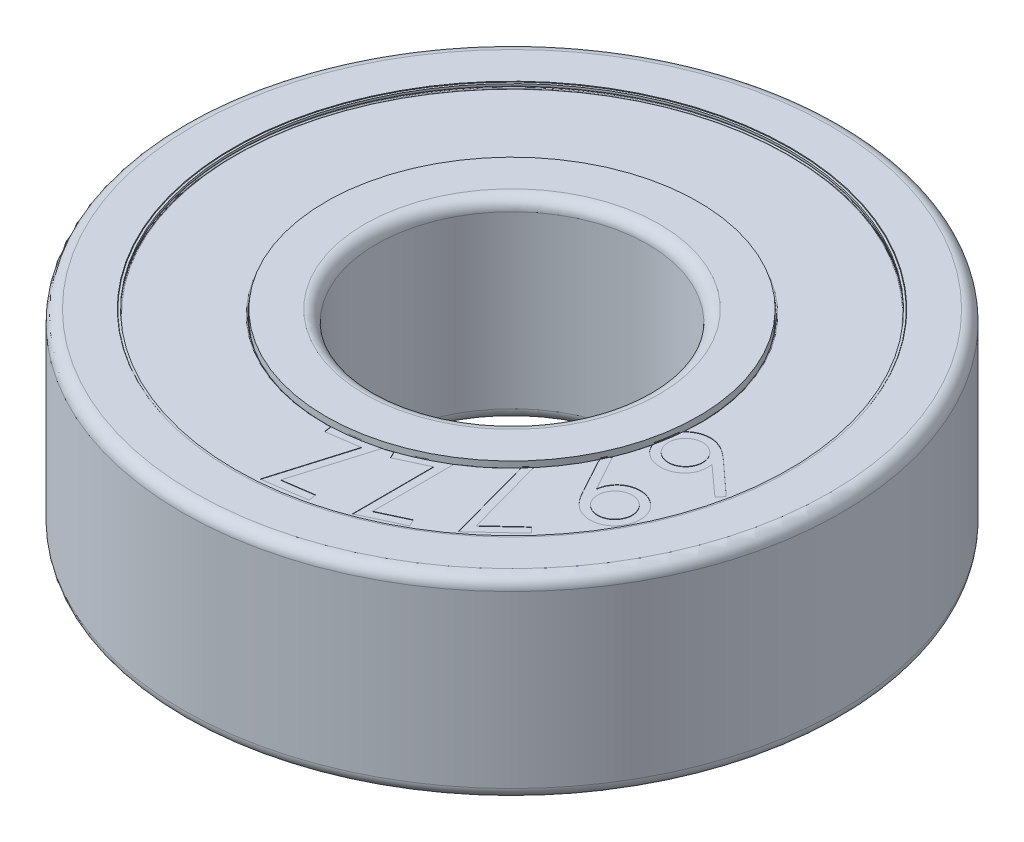
SolidWorks part; units mm, degrees
ref_plane "Front Plane" through (0, 0, 0) normal (0, 0, 1) x (1, 0, 0)
ref_plane "Top Plane" through (0, 0, 0) normal (0, 1, 0) x (1, 0, 0)
ref_plane "Right Plane" through (0, 0, 0) normal (1, 0, 0) x (0, 0, -1)
sketch "Croquis1" plane through (0, 0, 0) normal (1, 0, 0) x (0, 0, -1)
  line L0 (0, 5.6806) -> (0, -4.3073) construction
  line L1 (0, 0) -> (7.85, 0) construction
  line L2 (4.8, -2.5) -> (3.8, -2.5)
  line L3 (4.8, -2.5) -> (4.8, -0.9)
  line L4 (4.8, 2.5) -> (3.8, 2.5)
  line L5 (3.5, -2.2) -> (3.5, 2.2)
  line L6 (4.8, -2.5) -> (3.5, 2.5) construction
  line L7 (4.8, 2.5) -> (3.5, -2.5) construction
  line L8 (8.2, -2.5) -> (7.2, -2.5)
  line L9 (8.5, -2.2) -> (8.5, 2.2)
  line L10 (8.2, 2.5) -> (7.2, 2.5)
  line L11 (7.2, -2.5) -> (7.2, -2.45)
  line L12 (8.5, -2.5) -> (7.2, 2.5) construction
  line L13 (8.5, 2.5) -> (7.2, -2.5) construction
  line L14 (4.8, 0) -> (7.2, 0) construction
  line L15 (4.8, 0.9) -> (4.8, 2.5)
  line L16 (7.2, 0.9) -> (7.2, 2.1784)
  line L17 (7.2, -2.1784) -> (7.3884, -2.2877)
  line L18 (7.3884, -2.3525) -> (7.2, -2.45)
  line L19 (7.2, -2.1784) -> (7.2, -0.9)
  line L20 (7.2, 2.1784) -> (7.3884, 2.2877)
  line L21 (7.3884, 2.3525) -> (7.2, 2.45)
  line L22 (7.2, 2.45) -> (7.2, 2.5)
  line L23 (6, 0) -> (6, -0.5097) construction
  arc A0 (4.8, 0.9) -> (4.8, -0.9) centre (6, 0) ccw
  arc A1 (7.2, -0.9) -> (7.2, 0.9) centre (6, 0) ccw
  arc A2 (8.2, -2.5) -> (8.5, -2.2) centre (8.2, -2.2) ccw
  arc A3 (8.5, 2.2) -> (8.2, 2.5) centre (8.2, 2.2) ccw
  arc A4 (3.8, 2.5) -> (3.5, 2.2) centre (3.8, 2.2) ccw
  arc A5 (3.8, -2.5) -> (3.5, -2.2) centre (3.8, -2.2) cw
  arc A6 (7.3884, -2.3525) -> (7.3884, -2.2877) centre (7.3696, -2.3201) ccw
  arc A7 (7.3884, 2.3525) -> (7.3884, 2.2877) centre (7.3696, 2.3201) cw
  point P3 (4.15, 0)
  point P8 (7.85, 0)
  dimension "D6" = 3
  dimension "D7" = 0.3
  dimension "D1" = 3.5
  dimension "D2" = 8.5
  dimension "D3" = 5
  dimension "D4" = 1.3
  dimension "D5" = 1.3
  dimension "D8" = 0.05
  dimension "D9" = 6
revolve "Revolución1" add sketch "Croquis1" angle 360 about L0
sketch "Croquis3" plane through (0, 0, 0) normal (1, 0, 0) x (0, 0, -1)
  line L0 (0, 2.5) -> (0, -2.5) construction
  line L2 (-3.8, -2.5) -> (3.8, -2.5) construction
  line L3 (0, 0) -> (8.4869, 0) construction
  line L4 (3.8, 2.5) -> (-3.8, 2.5) construction
  line L5 (6, 2.5) -> (6, -2.5) construction
  line L6 (6, 1.475) -> (6, -1.475)
  arc A1 (6, -1.475) -> (6, 1.475) centre (6, 0) ccw
  point P2 (6, 0)
  dimension "D3" = 2.95
  dimension "D1" = 6
  dimension "D2" = 5
revolve "Revolución3" add sketch "Croquis3" angle 360 about L5
sketch "Croquis4" plane through (0, 0, 0) normal (1, 0, 0) x (0, 0, -1)
  line L0 (7.1909, -2.4866) -> (7.1909, -2.4681)
  line L1 (7.207, -2.4416) -> (7.387, -2.3472)
  line L2 (7.3881, -2.2947) -> (7.2209, -2.1972)
  line L3 (7.1799, -2.208) -> (7.1217, -2.3079)
  line L4 (7.0957, -2.3228) -> (4.8868, -2.3228)
  line L5 (4.8579, -2.3012) -> (4.8496, -2.2725)
  line L6 (4.8496, -2.2725) -> (4.8016, -2.2864)
  line L7 (4.8016, -2.2864) -> (4.8204, -2.3512)
  line L8 (4.8492, -2.3728) -> (7.1245, -2.3728)
  line L9 (7.1504, -2.3579) -> (7.1971, -2.2777)
  line L10 (7.2382, -2.2669) -> (7.2833, -2.2932)
  line L11 (7.2822, -2.3457) -> (7.157, -2.4113)
  line L12 (7.1409, -2.4379) -> (7.1409, -2.4866)
  line L13 (7.1409, -2.4866) -> (7.1909, -2.4866)
  line L14 (0, 0) -> (8.2183, 0) construction
  line L15 (5.0552, -1.2107) -> (5.0552, -1.3218)
  line L16 (-7.2, -2.45) -> (7.2, -2.45) construction
  line L17 (6.8464, 1.2792) -> (6.8464, 1.3848)
  line L18 (0, 1.5186) -> (0, -1.2233) construction
  line L19 (6.8464, -1.2792) -> (6.8464, -1.3848)
  line L20 (5.0552, 1.2107) -> (5.0552, 1.3218)
  line L21 (7.1409, 2.4866) -> (7.1909, 2.4866)
  line L22 (7.1409, 2.4379) -> (7.1409, 2.4866)
  line L23 (7.2822, 2.3457) -> (7.157, 2.4113)
  line L24 (7.2382, 2.2669) -> (7.2833, 2.2932)
  line L25 (7.1504, 2.3579) -> (7.1971, 2.2777)
  line L26 (4.8492, 2.3728) -> (7.1245, 2.3728)
  line L27 (4.8016, 2.2864) -> (4.8204, 2.3512)
  line L28 (4.8496, 2.2725) -> (4.8016, 2.2864)
  line L29 (4.8579, 2.3012) -> (4.8496, 2.2725)
  line L30 (7.0957, 2.3228) -> (4.8868, 2.3228)
  line L31 (7.1799, 2.208) -> (7.1217, 2.3079)
  line L32 (7.3881, 2.2947) -> (7.2209, 2.1972)
  line L33 (7.207, 2.4416) -> (7.387, 2.3472)
  line L34 (7.1909, 2.4866) -> (7.1909, 2.4681)
  arc A0 (4.8868, -2.3228) -> (4.8579, -2.3012) centre (4.8868, -2.2928) cw
  arc A1 (4.8204, -2.3512) -> (4.8492, -2.3728) centre (4.8492, -2.3428) ccw
  arc A2 (7.1971, -2.2777) -> (7.2382, -2.2669) centre (7.2231, -2.2928) cw
  arc A3 (7.2209, -2.1972) -> (7.1799, -2.208) centre (7.2058, -2.2231) ccw
  arc A4 (7.1909, -2.4681) -> (7.207, -2.4416) centre (7.2209, -2.4681) cw
  arc A5 (7.157, -2.4113) -> (7.1409, -2.4379) centre (7.1709, -2.4379) ccw
  arc A6 (7.2833, -2.2932) -> (7.2822, -2.3457) centre (7.2682, -2.3191) cw
  arc A7 (7.387, -2.3472) -> (7.3881, -2.2947) centre (7.373, -2.3206) ccw
  arc A8 (7.1245, -2.3728) -> (7.1504, -2.3579) centre (7.1245, -2.3428) ccw
  arc A9 (7.1217, -2.3079) -> (7.0957, -2.3228) centre (7.0957, -2.2928) cw
  arc A10 (5.0681, -1.3465) -> (6.8316, -1.4106) centre (6, 0) ccw
  arc A11 (5.1032, -1.1868) -> (6.8002, -1.2539) centre (6, 0) ccw
  arc A12 (6.8464, -1.3848) -> (6.8316, -1.4106) centre (6.8164, -1.3848) cw
  arc A13 (6.8002, -1.2539) -> (6.8464, -1.2792) centre (6.8164, -1.2792) cw
  arc A14 (5.0681, -1.3465) -> (5.0552, -1.3218) centre (5.0852, -1.3218) cw
  arc A15 (5.0552, -1.2107) -> (5.1032, -1.1868) centre (5.0852, -1.2107) cw
  arc A16 (5.0552, 1.2107) -> (5.1032, 1.1868) centre (5.0852, 1.2107) ccw
  arc A17 (5.0681, 1.3465) -> (5.0552, 1.3218) centre (5.0852, 1.3218) ccw
  arc A18 (6.8002, 1.2539) -> (6.8464, 1.2792) centre (6.8164, 1.2792) ccw
  arc A19 (6.8464, 1.3848) -> (6.8316, 1.4106) centre (6.8164, 1.3848) ccw
  arc A20 (5.1032, 1.1868) -> (6.8002, 1.2539) centre (6, 0) cw
  arc A21 (5.0681, 1.3465) -> (6.8316, 1.4106) centre (6, 0) cw
  arc A22 (7.1217, 2.3079) -> (7.0957, 2.3228) centre (7.0957, 2.2928) ccw
  arc A23 (7.1245, 2.3728) -> (7.1504, 2.3579) centre (7.1245, 2.3428) cw
  arc A24 (7.387, 2.3472) -> (7.3881, 2.2947) centre (7.373, 2.3206) cw
  arc A25 (7.2833, 2.2932) -> (7.2822, 2.3457) centre (7.2682, 2.3191) ccw
  arc A26 (7.157, 2.4113) -> (7.1409, 2.4379) centre (7.1709, 2.4379) cw
  arc A27 (7.1909, 2.4681) -> (7.207, 2.4416) centre (7.2209, 2.4681) ccw
  arc A28 (7.2209, 2.1972) -> (7.1799, 2.208) centre (7.2058, 2.2231) cw
  arc A29 (7.1971, 2.2777) -> (7.2382, 2.2669) centre (7.2231, 2.2928) ccw
  arc A30 (4.8204, 2.3512) -> (4.8492, 2.3728) centre (4.8492, 2.3428) cw
  arc A31 (4.8868, 2.3228) -> (4.8579, 2.3012) centre (4.8868, 2.2928) ccw
  point P41 (7.1909, -2.45)
  point P101 (7.1909, 2.45)
  dimension "D7" = 4.8496
  dimension "D9" = 4.8579
  dimension "D10" = 5.0552
  dimension "D11" = 6.8002
  dimension "D12" = 7.0957
  dimension "D13" = 7.1217
  dimension "D1" = 0.03
  dimension "D2" = 1.6375
  dimension "D3" = 1.4875
  dimension "D4" = 4.8016
  dimension "D5" = 4.8204
  dimension "D6" = 4.8492
  dimension "D8" = 6
  dimension "D14" = 7.1245
  dimension "D15" = 7.1409
  dimension "D16" = 7.157
  dimension "D17" = 7.2682
  dimension "D18" = 7.373
  dimension "D19" = 2.4866
revolve "Revolución4" add sketch "Croquis4" angle 360 about L18
sketch "Croquis6" plane through (0, 2.3728, 0) normal (0, 1, 0) x (1, 0, 0)
  text T0 "697ZZ" font "Century Gothic" height in points 8
extrude "Cortar-Extruir1" cut sketch "Croquis6" against normal blind 0.01
